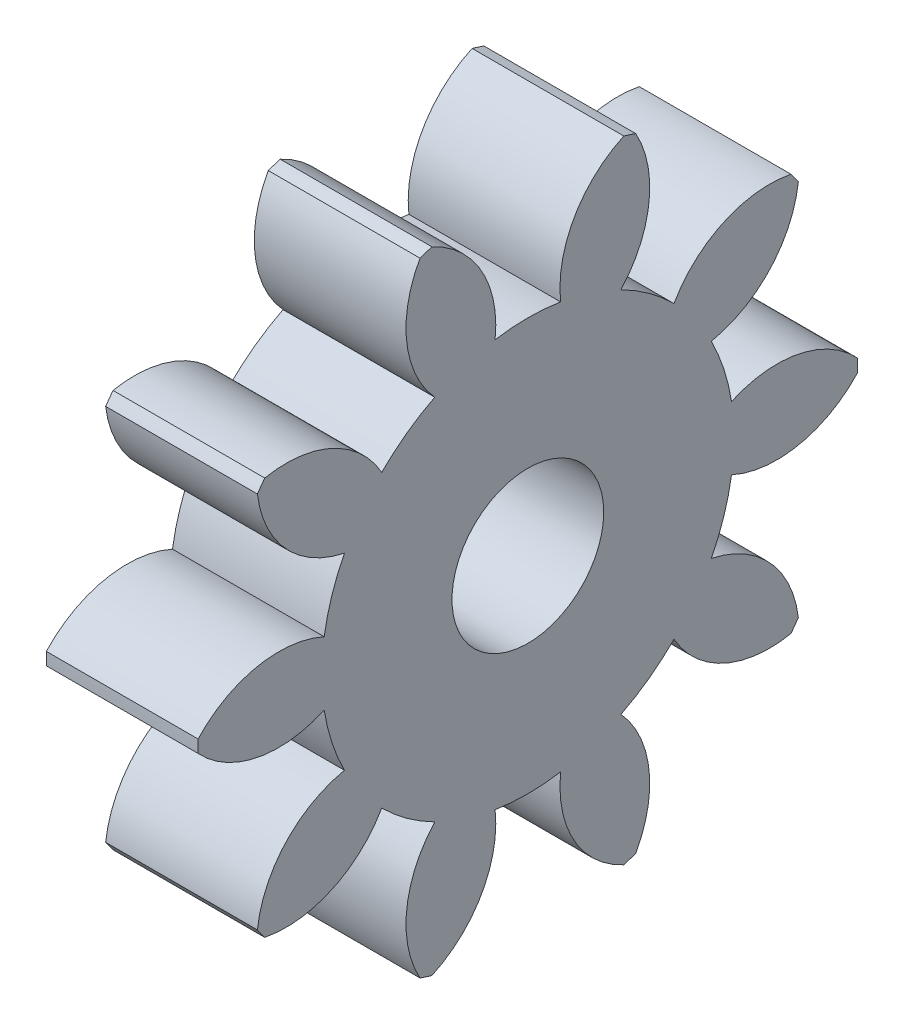
SolidWorks part; units mm, degrees
ref_plane "Plane1" through (0, 0, 0) normal (0, 0, 1) x (1, 0, 0)
ref_plane "Plane2" through (0, 0, 0) normal (0, 1, 0) x (1, 0, 0)
ref_plane "Plane3" through (0, 0, 0) normal (1, 0, 0) x (0, 0, -1)
sketch "HoldingSke" plane through (0, 0, 0) normal (0, 1, 0) x (1, 0, 0)
  line L0 (0, 0) -> (300.1694, -52.928)
  line L1 (-15, 0) -> (100, 0) construction
  line L2 (0, 0) -> (-2.1039, 2.3779)
  line L3 (0, 0) -> (-11.863, 4.5341)
  line L4 (0, 0) -> (8.5048, 1.4996)
  line L5 (0, 0) -> (-47.5972, -17.7524)
  line L6 (0, 0) -> (-4.8428, -3.2675)
  line L7 (-2.1039, 2.3779) -> (8.8308, 51.9871)
  line L8 (-76.2, 54.61) -> (-69.596, 54.61)
  line L9 (-71.009, 38.7566) -> (-53.1078, 45.2721)
  line L10 (-76.2, 71.12) -> (104.1128, 71.12)
  line L11 (0, 0) -> (-5.842, 0)
  line L12 (-76.2, 101.6) -> (-76.1147, 101.6)
  line L13 (24.9733, 27.94) -> (52.9518, 28.4284)
  line L14 (24.9733, 27.94) -> (24.9746, 27.94)
  line L15 (24.9733, 27.94) -> (100.4006, 29.5858)
  circle A0 centre (0, 0) radius 3.175
  circle A1 centre (0, 0) radius 7.9362
  circle A2 centre (0, 0) radius 38.1
  circle A3 centre (0, 0) radius 3.175
  dimension "MHD" = 15.8725
  dimension "Hub_dia" = 76.2
  dimension "Bore" = 6.35
  dimension "MBD" = 6.35
  dimension "Num_teeth" = 10
  dimension "Pitch" = 304.8
  dimension "Overall_len" = 50.8
  dimension "Show_teeth" = 10
  dimension "Thickness" = 5.842
  dimension "OAL" = 50.8001
  dimension "T_dim" = 6.604
  dimension "Ap" = 20
  dimension "H" = 19.05
  dimension "Pitch_radius" = 180.3128
  dimension "Width" = 5.842
  dimension "Backlash" = 0.0853
  dimension "Addendum_fac" = 1
  dimension "Dedendum_fac" = 1.25
  dimension "Clearance_fac" = 0.25
  dimension "Dedendum_add" = 0.0013
sketch "BasProSke" plane through (0, 0, 0) normal (0, 1, 0) x (1, 0, 0)
  line L0 (-10, 0) -> (60, 0) construction
  line L1 (0, 0) -> (0, 12.7)
  line L2 (0, 0) -> (5.842, 0)
  line L3 (5.842, 0) -> (5.842, 12.7)
  line L4 (5.842, 12.7) -> (0, 12.7)
  dimension "Thickness" = 5.842
  dimension "Diameter" = 25.4
revolve "Base-Revolve" add sketch "BasProSke" angle 360 about L0
sketch "TooCutSke" plane through (0, 0, 0) normal (1, 0, 0) x (0, 0, -1)
  line L1 (0, 0) -> (0, 107) construction
  line L2 (0, 0) -> (-1.8046, 10.4283) construction
  line L3 (0, 0) -> (-6.4743, 19.9258) construction
  line L4 (-1.8046, 10.4283) -> (-3.2371, 9.9629) construction
  arc A0 (1.2611, 7.8354) -> (-1.2611, 7.8354) centre (0, 0) ccw
  arc A1 (3.7293, 12.1667) -> (-3.7293, 12.1667) centre (0, 0) ccw
  circle A2 centre (0, 0) radius 10.5833 construction
  circle A3 centre (0, 0) radius 9.9451 construction
  arc A4 (-1.2611, 7.8354) -> (-3.7293, 12.1667) centre (-5.468, 8.3069) ccw
  arc A5 (3.7293, 12.1667) -> (1.2611, 7.8354) centre (5.468, 8.3069) ccw
  dimension "Root_dia" = 15.8725
  dimension "Overcut_dia" = 25.4508
  dimension "Pitch_dia" = 21.1667
  dimension "Base_dia" = 19.8902
  dimension "Flank_rad" = 4.2333
  dimension "Half_ang" = 18
  dimension "Half_CT" = 1.5062
extrude "ToothCut" cut sketch "TooCutSke" along normal through all
fillet "Breaks" [suppressed] radius 0.0423
fillet "RootFillets" [suppressed] radius 0.5304
pattern_circular "TeethCuts" count 10 every 36 about axis through (-10, 0, 0) along (1, 0, 0) of "ToothCut", "RootFillets", "Breaks"
sketch "HubNeaOneSke" plane through (0, 0, 0) normal (-1, 0, 0) x (0, 0, 1)
  circle A0 centre (0, 0) radius 7.9362
  dimension "Diameter" = 15.8725
extrude "HubNearOne" [suppressed] add sketch "HubNeaOneSke" along normal blind 44.9581
sketch "HubNeaBotSke" plane through (0, 0, 0) normal (-1, 0, 0) x (0, 0, 1)
  circle A0 centre (0, 0) radius 7.9362
  dimension "Diameter" = 15.8725
extrude "HubNearBoth" [suppressed] add sketch "HubNeaBotSke" along normal blind 22.479
ref_plane "FarPln" through (5.842, 0, 0) normal (1, 0, 0) x (0, 0, -1)
sketch "HubFarSke" plane through (5.842, 0, 0) normal (1, 0, 0) x (0, 0, -1)
  circle A0 centre (0, 0) radius 7.9362
  dimension "Diameter" = 15.8725
extrude "HubFar" [suppressed] add sketch "HubFarSke" along normal blind 22.479
sketch "BorSke" plane through (0, 0, 0) normal (1, 0, 0) x (0, 0, -1)
  circle A0 centre (0, 0) radius 3.175
  dimension "Diameter" = 6.35
extrude "Bore" cut sketch "BorSke" along normal mid plane 101.6001
sketch "KeySke" plane through (0, 0, 0) normal (1, 0, 0) x (0, 0, -1)
  line L0 (-0.127, 0) -> (-0.127, 3.429)
  line L1 (-0.127, 3.429) -> (0.127, 3.429)
  line L2 (0.127, 3.429) -> (0.127, 0)
  line L3 (0, 0) -> (0, 34) construction
  line L4 (-0.127, 0) -> (0.127, 0)
  dimension "Offset" = 3.429
  dimension "Width" = 0.254
extrude "Keyway" [suppressed] cut sketch "KeySke" along normal mid plane 101.6001
pattern_circular "Keyway2" [suppressed] count 2 every 90 about axis through (-10, 0, 0) along (1, 0, 0)
sketch "Sketch1" plane through (5.842, 0, 0) normal (1, 0, 0) x (0, 0, -1)
  circle A0 centre (0, 0) radius 2.921
  circle A1 centre (0, 0) radius 3.175
  dimension "D1" = 5.842
extrude "Boss-Extrude1" add sketch "Sketch1" against normal up to surface (5.842 mm away) up to face at (0, 0, -3.175)
equation "' \"Pitch@HoldingSke\" = 4"
equation "' \"Num_teeth@HoldingSke\" = 12"
equation "' \"Ap@HoldingSke\" =  20"
equation "' \"Ap@HoldingSke\" = 20"
equation "' \"Width@HoldingSke\" = 0.5"
equation "' \"Hub_dia@HoldingSke\"= 1"
equation "' \"Hub_dia@HoldingSke\" = 1"
equation "' \"Overall_len@HoldingSke\" = 1.0"
equation "' \"Bore@HoldingSke\" = 0.75"
equation "' \"T_dim@HoldingSke\" = 0.85"
equation "' \"Width@KeySke\" = 0.25"
equation "' \"Show_teeth@HoldingSke\" = 13"
equation "' \"Backlash@HoldingSke\" = 0.009"
equation "' \"Addendum_fac@HoldingSke\" = 1.0"
equation "' \"Dedendum_fac@HoldingSke\" = 1.25"
equation "' \"Dedendum_add@HoldingSke\" = 0.00005"
equation "' \"Clearance_fac@HoldingSke\" = 0.25"
equation "' \"Pitch@HoldingSke\" = 0.5"
equation "' \"Num_teeth@HoldingSke\" = 23"
equation "' \"Show_teeth@HoldingSke\" = 23"
equation "' \"Backlash@HoldingSke\" = 0.0375"
equation "\"Overcut_dia@TooCutSke\" = (\"Num_teeth@HoldingSke\" + 2 * \"Addendum_fac@HoldingSke\") / \"Pitch@HoldingSke\" + 0.002"
equation "\"Pitch_dia@TooCutSke\" = \"Num_teeth@HoldingSke\" / \"Pitch@HoldingSke\""
equation "\"Base_dia@TooCutSke\" = \"Num_teeth@HoldingSke\" / \"Pitch@HoldingSke\" * cos((\"Ap@HoldingSke\"  * 3.14159265 / 180))"
equation "\"Root_dia@TooCutSke\" = (\"Num_teeth@HoldingSke\" + 2) / \"Pitch@HoldingSke\" - 2 * (\"Addendum_fac@HoldingSke\" + \"Dedendum_fac@HoldingSke\") / \"Pitch@HoldingSke\" - \"Dedendum_add@HoldingSke\" * 2"
equation "\"Half_ang@TooCutSke\" = 180 / \"Num_teeth@HoldingSke\""
equation "\"Half_CT@TooCutSke\" = \"Num_teeth@HoldingSke\" / \"Pitch@HoldingSke\" * sin((3.14159265 / 2 / \"Num_teeth@HoldingSke\")) / 2 - 7 * \"Backlash@HoldingSke\" / 4"
equation "\"Flank_rad@TooCutSke\" = \"Num_teeth@HoldingSke\" / \"Pitch@HoldingSke\" / 5"
equation "\"Radius@RootFillets\" = \"Clearance_fac@HoldingSke\" / \"Pitch@HoldingSke\" + \"Dedendum_add@HoldingSke\""
equation "\"Break_rad@Breaks\" = 0.02 / \"Pitch@HoldingSke\""
equation "\"Thickness@HoldingSke\" = \"Width@HoldingSke\""
equation "\"OAL@HoldingSke\" = \"Thickness@HoldingSke\""
equation "\"MHD@HoldingSke\" = (\"Num_teeth@HoldingSke\" + 2) / \"Pitch@HoldingSke\" - 2 * (\"Addendum_fac@HoldingSke\" + \"Dedendum_fac@HoldingSke\")  / \"Pitch@HoldingSke\" - \"Dedendum_add@HoldingSke\" * 2"
equation "\"MBD@HoldingSke\" = (\"Num_teeth@HoldingSke\" + 2) / \"Pitch@HoldingSke\" - 2 * (\"Addendum_fac@HoldingSke\" + \"Dedendum_fac@HoldingSke\")  / \"Pitch@HoldingSke\" - \"Dedendum_add@HoldingSke\" * 2 - 0.002"
equation "\"MHD@HoldingSke\" = ((sgn( \"MHD@HoldingSke\" - \"Hub_dia@HoldingSke\" )-1)*( \"MHD@HoldingSke\" - \"Hub_dia@HoldingSke\" ))/-2+ \"Hub_dia@HoldingSke\""
equation "\"MBD@HoldingSke\" = ((sgn( \"MBD@HoldingSke\" - \"Bore@HoldingSke\" )-1)*( \"MBD@HoldingSke\" - \"Bore@HoldingSke\" ))/-2+ \"Bore@HoldingSke\""
equation "\"OAL@HoldingSke\" = ((sgn( \"OAL@HoldingSke\" - \"Overall_len@HoldingSke\" )+1)*( \"OAL@HoldingSke\" - \"Overall_len@HoldingSke\" ))/2 + \"Overall_len@HoldingSke\" + 0.000002"
equation "\"Num_teeth@TeethCuts\" = int( \"Show_teeth@HoldingSke\" ) + 1"
equation "\"Num_teeth@TeethCuts\" = ((sgn( \"Num_teeth@TeethCuts\" - \"Num_teeth@HoldingSke\" )-1)*( \"Num_teeth@TeethCuts\" - \"Num_teeth@HoldingSke\" ))/-2+ \"Num_teeth@HoldingSke\""
equation "\"Num_teeth@TeethCuts\" = ((sgn( \"Num_teeth@TeethCuts\" - 2.0)+1)*( \"Num_teeth@TeethCuts\" - 2.0))/2 +2.0"
equation "\"Angle@TeethCuts\" = 360.0 / \"Num_teeth@HoldingSke\""
equation "\"Diameter@BasProSke\" = (\"Num_teeth@HoldingSke\" + 2 * \"Addendum_fac@HoldingSke\") / \"Pitch@HoldingSke\""
equation "\"Thickness@BasProSke\"  = \"Thickness@HoldingSke\""
equation "' \"Fillet_rad@BasProSke\" =  \"Thickness@HoldingSke\" * 0.05"
equation "' \"Fillet_rad@BasProSke\" = \"Thickness@HoldingSke\" * 0.05"
equation "\"MHD@HoldingSke\" = ((sgn( \"MHD@HoldingSke\" - \"Root_dia@TooCutSke\" )-1)*( \"MHD@HoldingSke\" - \"Root_dia@TooCutSke\" ))/-2+ \"Root_dia@TooCutSke\""
equation "\"Diameter@HubNeaOneSke\" = \"MHD@HoldingSke\""
equation "\"Length@HubNearOne\" = \"OAL@HoldingSke\" - \"Thickness@BasProSke\""
equation "\"Diameter@HubNeaBotSke\" = \"MHD@HoldingSke\""
equation "\"Length@HubNearBoth\" = ( \"OAL@HoldingSke\" - \"Thickness@BasProSke\" ) / 2.0"
equation "\"Thickness@FarPln\" = \"Thickness@BasProSke\""
equation "\"Diameter@HubFarSke\" = \"MHD@HoldingSke\""
equation "\"Length@HubFar\" = ( \"OAL@HoldingSke\" - \"Thickness@BasProSke\" ) / 2.0"
equation "\"Diameter@BorSke\" = \"MBD@HoldingSke\""
equation "\"D1@Bore\" = \"OAL@HoldingSke\" * 2.0"
equation "\"D1@Keyway\" = \"OAL@HoldingSke\" * 2.0"
equation "\"Offset@KeySke\" = \"T_dim@HoldingSke\" - \"MBD@HoldingSke\" / 2.0"
